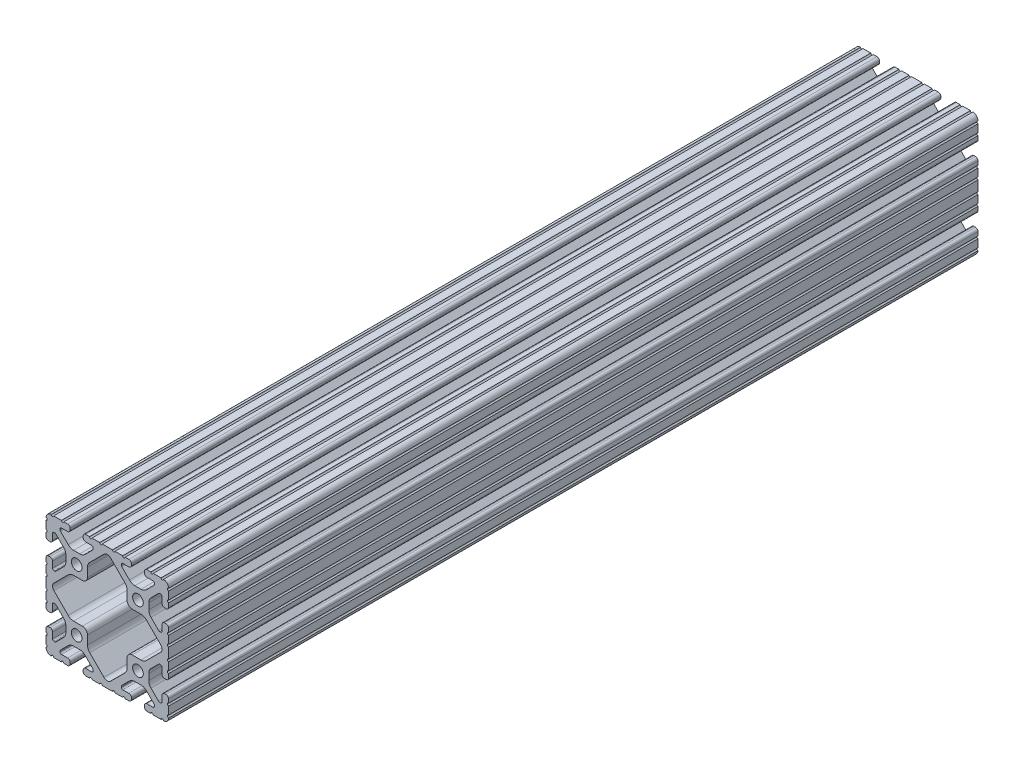
SolidWorks part; units mm, degrees
material "6105-T5 Aluminum"
ref_plane "Front Plane" through (0, 0, 0) normal (0, 0, 1) x (1, 0, 0)
ref_plane "Top Plane" through (0, 0, 0) normal (0, 1, 0) x (1, 0, 0)
ref_plane "Right Plane" through (0, 0, 0) normal (1, 0, 0) x (0, 0, -1)
sketch "Sketch1" plane through (0, 0, 0) normal (0, 0, 1) x (1, 0, 0)
  line L0 (15.487, 12.312) -> (20.9469, 12.312)
  line L1 (24.3055, 10.9208) -> (33.1609, 2.0655)
  line L2 (33.1609, -2.0655) -> (24.3055, -10.9208)
  line L3 (20.9469, -12.312) -> (15.487, -12.312)
  line L4 (12.312, -15.487) -> (12.312, -20.9469)
  line L5 (10.9208, -24.3055) -> (2.0655, -33.1609)
  line L6 (-2.0655, -33.1609) -> (-10.9208, -24.3055)
  line L7 (-12.312, -20.9469) -> (-12.312, -15.487)
  line L8 (-15.487, -12.312) -> (-20.9469, -12.312)
  line L9 (-24.3055, -10.9208) -> (-33.1609, -2.0655)
  line L10 (-33.1609, 2.0655) -> (-24.3055, 10.9208)
  line L11 (-20.9469, 12.312) -> (-15.487, 12.312)
  line L12 (-12.312, 15.487) -> (-12.312, 20.9469)
  line L13 (-10.9208, 24.3055) -> (-2.0655, 33.1609)
  line L14 (2.0655, 33.1609) -> (10.9208, 24.3055)
  line L15 (12.312, 20.9469) -> (12.312, 15.487)
  line L16 (-38.1, 3.2004) -> (-38.1, -3.2004)
  line L17 (-38.1, -4.7244) -> (-38.1, -9.5504)
  line L18 (-38.1, -11.0744) -> (-38.1, -13.4112)
  line L19 (-36.5252, -14.986) -> (-35.6108, -14.986)
  line L20 (-34.036, -13.4112) -> (-34.036, -9.652)
  line L21 (-33.147, -8.763) -> (-32.5789, -8.763)
  line L22 (-31.9503, -9.0234) -> (-27.1792, -13.7945)
  line L23 (-25.788, -17.1531) -> (-25.788, -20.9469)
  line L24 (-27.1792, -24.3055) -> (-31.9503, -29.0766)
  line L25 (-32.5789, -29.337) -> (-33.147, -29.337)
  line L26 (-34.036, -28.448) -> (-34.036, -24.6888)
  line L27 (-35.6108, -23.114) -> (-36.5252, -23.114)
  line L28 (-38.1, -24.6888) -> (-38.1, -27.0256)
  line L29 (-38.1, -28.5496) -> (-38.1, -33.3756)
  line L30 (-38.1, -34.8996) -> (-38.1, -34.925)
  line L31 (-34.925, -38.1) -> (-34.8996, -38.1)
  line L32 (-33.3756, -38.1) -> (-28.5496, -38.1)
  line L33 (-27.0256, -38.1) -> (-24.6888, -38.1)
  line L34 (-23.114, -36.5252) -> (-23.114, -35.6108)
  line L35 (-24.6888, -34.036) -> (-28.448, -34.036)
  line L36 (-29.337, -33.147) -> (-29.337, -32.5789)
  line L37 (-29.0766, -31.9503) -> (-24.3055, -27.1792)
  line L38 (-20.9469, -25.788) -> (-17.1531, -25.788)
  line L39 (-13.7945, -27.1792) -> (-9.0234, -31.9503)
  line L40 (-8.763, -32.5789) -> (-8.763, -33.147)
  line L41 (-9.652, -34.036) -> (-13.4112, -34.036)
  line L42 (-14.986, -35.6108) -> (-14.986, -36.5252)
  line L43 (-13.4112, -38.1) -> (-11.0744, -38.1)
  line L44 (-9.5504, -38.1) -> (-4.7244, -38.1)
  line L45 (-3.2004, -38.1) -> (3.2004, -38.1)
  line L46 (4.7244, -38.1) -> (9.5504, -38.1)
  line L47 (11.0744, -38.1) -> (13.4112, -38.1)
  line L48 (14.986, -36.5252) -> (14.986, -35.6108)
  line L49 (13.4112, -34.036) -> (9.652, -34.036)
  line L50 (8.763, -33.147) -> (8.763, -32.5789)
  line L51 (9.0234, -31.9503) -> (13.7945, -27.1792)
  line L52 (17.1531, -25.788) -> (20.9469, -25.788)
  line L53 (24.3055, -27.1792) -> (29.0766, -31.9503)
  line L54 (29.337, -32.5789) -> (29.337, -33.147)
  line L55 (28.448, -34.036) -> (24.6888, -34.036)
  line L56 (23.114, -35.6108) -> (23.114, -36.5252)
  line L57 (24.6888, -38.1) -> (27.0256, -38.1)
  line L58 (28.5496, -38.1) -> (33.3756, -38.1)
  line L59 (34.8996, -38.1) -> (34.925, -38.1)
  line L60 (38.1, -34.925) -> (38.1, -34.8996)
  line L61 (38.1, -33.3756) -> (38.1, -28.5496)
  line L62 (38.1, -27.0256) -> (38.1, -24.6888)
  line L63 (36.5252, -23.114) -> (35.6108, -23.114)
  line L64 (34.036, -24.6888) -> (34.036, -28.448)
  line L65 (33.147, -29.337) -> (32.5789, -29.337)
  line L66 (31.9503, -29.0766) -> (27.1792, -24.3055)
  line L67 (25.788, -20.9469) -> (25.788, -17.1531)
  line L68 (27.1792, -13.7945) -> (31.9503, -9.0234)
  line L69 (32.5789, -8.763) -> (33.147, -8.763)
  line L70 (34.036, -9.652) -> (34.036, -13.4112)
  line L71 (35.6108, -14.986) -> (36.5252, -14.986)
  line L72 (38.1, -13.4112) -> (38.1, -11.0744)
  line L73 (38.1, -9.5504) -> (38.1, -4.7244)
  line L74 (38.1, -3.2004) -> (38.1, 3.2004)
  line L75 (38.1, 4.7244) -> (38.1, 9.5504)
  line L76 (38.1, 11.0744) -> (38.1, 13.4112)
  line L77 (36.5252, 14.986) -> (35.6108, 14.986)
  line L78 (34.036, 13.4112) -> (34.036, 9.652)
  line L79 (33.147, 8.763) -> (32.5789, 8.763)
  line L80 (31.9503, 9.0234) -> (27.1792, 13.7945)
  line L81 (25.788, 17.1531) -> (25.788, 20.9469)
  line L82 (27.1792, 24.3055) -> (31.9503, 29.0766)
  line L83 (32.5789, 29.337) -> (33.147, 29.337)
  line L84 (34.036, 28.448) -> (34.036, 24.6888)
  line L85 (35.6108, 23.114) -> (36.5252, 23.114)
  line L86 (38.1, 24.6888) -> (38.1, 27.0256)
  line L87 (38.1, 28.5496) -> (38.1, 33.3756)
  line L88 (38.1, 34.8996) -> (38.1, 34.925)
  line L89 (34.925, 38.1) -> (34.8996, 38.1)
  line L90 (33.3756, 38.1) -> (28.5496, 38.1)
  line L91 (27.0256, 38.1) -> (24.6888, 38.1)
  line L92 (23.114, 36.5252) -> (23.114, 35.6108)
  line L93 (24.6888, 34.036) -> (28.448, 34.036)
  line L94 (29.337, 33.147) -> (29.337, 32.5789)
  line L95 (29.0766, 31.9503) -> (24.3055, 27.1792)
  line L96 (20.9469, 25.788) -> (17.1531, 25.788)
  line L97 (13.7945, 27.1792) -> (9.0234, 31.9503)
  line L98 (8.763, 32.5789) -> (8.763, 33.147)
  line L99 (9.652, 34.036) -> (13.4112, 34.036)
  line L100 (14.986, 35.6108) -> (14.986, 36.5252)
  line L101 (13.4112, 38.1) -> (11.0744, 38.1)
  line L102 (9.5504, 38.1) -> (4.7244, 38.1)
  line L103 (3.2004, 38.1) -> (-3.2004, 38.1)
  line L104 (-4.7244, 38.1) -> (-9.5504, 38.1)
  line L105 (-11.0744, 38.1) -> (-13.4112, 38.1)
  line L106 (-14.986, 36.5252) -> (-14.986, 35.6108)
  line L107 (-13.4112, 34.036) -> (-9.652, 34.036)
  line L108 (-8.763, 33.147) -> (-8.763, 32.5789)
  line L109 (-9.0234, 31.9503) -> (-13.7945, 27.1792)
  line L110 (-17.1531, 25.788) -> (-20.9469, 25.788)
  line L111 (-24.3055, 27.1792) -> (-29.0766, 31.9503)
  line L112 (-29.337, 32.5789) -> (-29.337, 33.147)
  line L113 (-28.448, 34.036) -> (-24.6888, 34.036)
  line L114 (-23.114, 35.6108) -> (-23.114, 36.5252)
  line L115 (-24.6888, 38.1) -> (-27.0256, 38.1)
  line L116 (-28.5496, 38.1) -> (-33.3756, 38.1)
  line L117 (-34.8996, 38.1) -> (-34.925, 38.1)
  line L118 (-38.1, 34.925) -> (-38.1, 34.8996)
  line L119 (-38.1, 33.3756) -> (-38.1, 28.5496)
  line L120 (-38.1, 27.0256) -> (-38.1, 24.6888)
  line L121 (-36.5252, 23.114) -> (-35.6108, 23.114)
  line L122 (-34.036, 24.6888) -> (-34.036, 28.448)
  line L123 (-33.147, 29.337) -> (-32.5789, 29.337)
  line L124 (-31.9503, 29.0766) -> (-27.1792, 24.3055)
  line L125 (-25.788, 20.9469) -> (-25.788, 17.1531)
  line L126 (-27.1792, 13.7945) -> (-31.9503, 9.0234)
  line L127 (-32.5789, 8.763) -> (-33.147, 8.763)
  line L128 (-34.036, 9.652) -> (-34.036, 13.4112)
  line L129 (-35.6108, 14.986) -> (-36.5252, 14.986)
  line L130 (-38.1, 13.4112) -> (-38.1, 11.0744)
  line L131 (-38.1, 9.5504) -> (-38.1, 4.7244)
  circle A0 centre (-19.05, 19.05) radius 3.3274
  circle A1 centre (-19.05, -19.05) radius 3.3274
  circle A2 centre (19.05, -19.05) radius 3.3274
  circle A3 centre (19.05, 19.05) radius 3.3274
  arc A4 (12.312, 15.487) -> (15.487, 12.312) centre (15.487, 15.487) ccw
  arc A5 (24.3055, 10.9208) -> (20.9469, 12.312) centre (20.9469, 7.5622) ccw
  arc A6 (33.1609, -2.0655) -> (33.1609, 2.0655) centre (31.0954, 0) ccw
  arc A7 (20.9469, -12.312) -> (24.3055, -10.9208) centre (20.9469, -7.5622) ccw
  arc A8 (15.487, -12.312) -> (12.312, -15.487) centre (15.487, -15.487) ccw
  arc A9 (10.9208, -24.3055) -> (12.312, -20.9469) centre (7.5622, -20.9469) ccw
  arc A10 (-2.0655, -33.1609) -> (2.0655, -33.1609) centre (0, -31.0954) ccw
  arc A11 (-12.312, -20.9469) -> (-10.9208, -24.3055) centre (-7.5622, -20.9469) ccw
  arc A12 (-12.312, -15.487) -> (-15.487, -12.312) centre (-15.487, -15.487) ccw
  arc A13 (-24.3055, -10.9208) -> (-20.9469, -12.312) centre (-20.9469, -7.5622) ccw
  arc A14 (-33.1609, 2.0655) -> (-33.1609, -2.0655) centre (-31.0954, 0) ccw
  arc A15 (-20.9469, 12.312) -> (-24.3055, 10.9208) centre (-20.9469, 7.5622) ccw
  arc A16 (-15.487, 12.312) -> (-12.312, 15.487) centre (-15.487, 15.487) ccw
  arc A17 (-10.9208, 24.3055) -> (-12.312, 20.9469) centre (-7.5622, 20.9469) ccw
  arc A18 (2.0655, 33.1609) -> (-2.0655, 33.1609) centre (0, 31.0954) ccw
  arc A19 (12.312, 20.9469) -> (10.9208, 24.3055) centre (7.5622, 20.9469) ccw
  arc A20 (-38.1, -4.7244) -> (-38.1, -3.2004) centre (-38.1, -3.9624) ccw
  arc A21 (-38.1, -11.0744) -> (-38.1, -9.5504) centre (-38.1, -10.3124) ccw
  arc A22 (-38.1, -13.4112) -> (-36.5252, -14.986) centre (-36.5252, -13.4112) ccw
  arc A23 (-35.6108, -14.986) -> (-34.036, -13.4112) centre (-35.6108, -13.4112) ccw
  arc A24 (-33.147, -8.763) -> (-34.036, -9.652) centre (-33.147, -9.652) ccw
  arc A25 (-31.9503, -9.0234) -> (-32.5789, -8.763) centre (-32.5789, -9.652) ccw
  arc A26 (-25.788, -17.1531) -> (-27.1792, -13.7945) centre (-30.5378, -17.1531) ccw
  arc A27 (-27.1792, -24.3055) -> (-25.788, -20.9469) centre (-30.5378, -20.9469) ccw
  arc A28 (-32.5789, -29.337) -> (-31.9503, -29.0766) centre (-32.5789, -28.448) ccw
  arc A29 (-34.036, -28.448) -> (-33.147, -29.337) centre (-33.147, -28.448) ccw
  arc A30 (-34.036, -24.6888) -> (-35.6108, -23.114) centre (-35.6108, -24.6888) ccw
  arc A31 (-36.5252, -23.114) -> (-38.1, -24.6888) centre (-36.5252, -24.6888) ccw
  arc A32 (-38.1, -28.5496) -> (-38.1, -27.0256) centre (-38.1, -27.7876) ccw
  arc A33 (-38.1, -34.8996) -> (-38.1, -33.3756) centre (-38.1, -34.1376) ccw
  arc A34 (-38.1, -34.925) -> (-34.925, -38.1) centre (-34.925, -34.925) ccw
  arc A35 (-33.3756, -38.1) -> (-34.8996, -38.1) centre (-34.1376, -38.1) ccw
  arc A36 (-27.0256, -38.1) -> (-28.5496, -38.1) centre (-27.7876, -38.1) ccw
  arc A37 (-24.6888, -38.1) -> (-23.114, -36.5252) centre (-24.6888, -36.5252) ccw
  arc A38 (-23.114, -35.6108) -> (-24.6888, -34.036) centre (-24.6888, -35.6108) ccw
  arc A39 (-29.337, -33.147) -> (-28.448, -34.036) centre (-28.448, -33.147) ccw
  arc A40 (-29.0766, -31.9503) -> (-29.337, -32.5789) centre (-28.448, -32.5789) ccw
  arc A41 (-20.9469, -25.788) -> (-24.3055, -27.1792) centre (-20.9469, -30.5378) ccw
  arc A42 (-13.7945, -27.1792) -> (-17.1531, -25.788) centre (-17.1531, -30.5378) ccw
  arc A43 (-8.763, -32.5789) -> (-9.0234, -31.9503) centre (-9.652, -32.5789) ccw
  arc A44 (-9.652, -34.036) -> (-8.763, -33.147) centre (-9.652, -33.147) ccw
  arc A45 (-13.4112, -34.036) -> (-14.986, -35.6108) centre (-13.4112, -35.6108) ccw
  arc A46 (-14.986, -36.5252) -> (-13.4112, -38.1) centre (-13.4112, -36.5252) ccw
  arc A47 (-9.5504, -38.1) -> (-11.0744, -38.1) centre (-10.3124, -38.1) ccw
  arc A48 (-3.2004, -38.1) -> (-4.7244, -38.1) centre (-3.9624, -38.1) ccw
  arc A49 (4.7244, -38.1) -> (3.2004, -38.1) centre (3.9624, -38.1) ccw
  arc A50 (11.0744, -38.1) -> (9.5504, -38.1) centre (10.3124, -38.1) ccw
  arc A51 (13.4112, -38.1) -> (14.986, -36.5252) centre (13.4112, -36.5252) ccw
  arc A52 (14.986, -35.6108) -> (13.4112, -34.036) centre (13.4112, -35.6108) ccw
  arc A53 (8.763, -33.147) -> (9.652, -34.036) centre (9.652, -33.147) ccw
  arc A54 (9.0234, -31.9503) -> (8.763, -32.5789) centre (9.652, -32.5789) ccw
  arc A55 (17.1531, -25.788) -> (13.7945, -27.1792) centre (17.1531, -30.5378) ccw
  arc A56 (24.3055, -27.1792) -> (20.9469, -25.788) centre (20.9469, -30.5378) ccw
  arc A57 (29.337, -32.5789) -> (29.0766, -31.9503) centre (28.448, -32.5789) ccw
  arc A58 (28.448, -34.036) -> (29.337, -33.147) centre (28.448, -33.147) ccw
  arc A59 (24.6888, -34.036) -> (23.114, -35.6108) centre (24.6888, -35.6108) ccw
  arc A60 (23.114, -36.5252) -> (24.6888, -38.1) centre (24.6888, -36.5252) ccw
  arc A61 (28.5496, -38.1) -> (27.0256, -38.1) centre (27.7876, -38.1) ccw
  arc A62 (34.8996, -38.1) -> (33.3756, -38.1) centre (34.1376, -38.1) ccw
  arc A63 (34.925, -38.1) -> (38.1, -34.925) centre (34.925, -34.925) ccw
  arc A64 (38.1, -33.3756) -> (38.1, -34.8996) centre (38.1, -34.1376) ccw
  arc A65 (38.1, -27.0256) -> (38.1, -28.5496) centre (38.1, -27.7876) ccw
  arc A66 (38.1, -24.6888) -> (36.5252, -23.114) centre (36.5252, -24.6888) ccw
  arc A67 (35.6108, -23.114) -> (34.036, -24.6888) centre (35.6108, -24.6888) ccw
  arc A68 (33.147, -29.337) -> (34.036, -28.448) centre (33.147, -28.448) ccw
  arc A69 (31.9503, -29.0766) -> (32.5789, -29.337) centre (32.5789, -28.448) ccw
  arc A70 (25.788, -20.9469) -> (27.1792, -24.3055) centre (30.5378, -20.9469) ccw
  arc A71 (27.1792, -13.7945) -> (25.788, -17.1531) centre (30.5378, -17.1531) ccw
  arc A72 (32.5789, -8.763) -> (31.9503, -9.0234) centre (32.5789, -9.652) ccw
  arc A73 (34.036, -9.652) -> (33.147, -8.763) centre (33.147, -9.652) ccw
  arc A74 (34.036, -13.4112) -> (35.6108, -14.986) centre (35.6108, -13.4112) ccw
  arc A75 (36.5252, -14.986) -> (38.1, -13.4112) centre (36.5252, -13.4112) ccw
  arc A76 (38.1, -9.5504) -> (38.1, -11.0744) centre (38.1, -10.3124) ccw
  arc A77 (38.1, -3.2004) -> (38.1, -4.7244) centre (38.1, -3.9624) ccw
  arc A78 (38.1, 4.7244) -> (38.1, 3.2004) centre (38.1, 3.9624) ccw
  arc A79 (38.1, 11.0744) -> (38.1, 9.5504) centre (38.1, 10.3124) ccw
  arc A80 (38.1, 13.4112) -> (36.5252, 14.986) centre (36.5252, 13.4112) ccw
  arc A81 (35.6108, 14.986) -> (34.036, 13.4112) centre (35.6108, 13.4112) ccw
  arc A82 (33.147, 8.763) -> (34.036, 9.652) centre (33.147, 9.652) ccw
  arc A83 (31.9503, 9.0234) -> (32.5789, 8.763) centre (32.5789, 9.652) ccw
  arc A84 (25.788, 17.1531) -> (27.1792, 13.7945) centre (30.5378, 17.1531) ccw
  arc A85 (27.1792, 24.3055) -> (25.788, 20.9469) centre (30.5378, 20.9469) ccw
  arc A86 (32.5789, 29.337) -> (31.9503, 29.0766) centre (32.5789, 28.448) ccw
  arc A87 (34.036, 28.448) -> (33.147, 29.337) centre (33.147, 28.448) ccw
  arc A88 (34.036, 24.6888) -> (35.6108, 23.114) centre (35.6108, 24.6888) ccw
  arc A89 (36.5252, 23.114) -> (38.1, 24.6888) centre (36.5252, 24.6888) ccw
  arc A90 (38.1, 28.5496) -> (38.1, 27.0256) centre (38.1, 27.7876) ccw
  arc A91 (38.1, 34.8996) -> (38.1, 33.3756) centre (38.1, 34.1376) ccw
  arc A92 (38.1, 34.925) -> (34.925, 38.1) centre (34.925, 34.925) ccw
  arc A93 (33.3756, 38.1) -> (34.8996, 38.1) centre (34.1376, 38.1) ccw
  arc A94 (27.0256, 38.1) -> (28.5496, 38.1) centre (27.7876, 38.1) ccw
  arc A95 (24.6888, 38.1) -> (23.114, 36.5252) centre (24.6888, 36.5252) ccw
  arc A96 (23.114, 35.6108) -> (24.6888, 34.036) centre (24.6888, 35.6108) ccw
  arc A97 (29.337, 33.147) -> (28.448, 34.036) centre (28.448, 33.147) ccw
  arc A98 (29.0766, 31.9503) -> (29.337, 32.5789) centre (28.448, 32.5789) ccw
  arc A99 (20.9469, 25.788) -> (24.3055, 27.1792) centre (20.9469, 30.5378) ccw
  arc A100 (13.7945, 27.1792) -> (17.1531, 25.788) centre (17.1531, 30.5378) ccw
  arc A101 (8.763, 32.5789) -> (9.0234, 31.9503) centre (9.652, 32.5789) ccw
  arc A102 (9.652, 34.036) -> (8.763, 33.147) centre (9.652, 33.147) ccw
  arc A103 (13.4112, 34.036) -> (14.986, 35.6108) centre (13.4112, 35.6108) ccw
  arc A104 (14.986, 36.5252) -> (13.4112, 38.1) centre (13.4112, 36.5252) ccw
  arc A105 (9.5504, 38.1) -> (11.0744, 38.1) centre (10.3124, 38.1) ccw
  arc A106 (3.2004, 38.1) -> (4.7244, 38.1) centre (3.9624, 38.1) ccw
  arc A107 (-4.7244, 38.1) -> (-3.2004, 38.1) centre (-3.9624, 38.1) ccw
  arc A108 (-11.0744, 38.1) -> (-9.5504, 38.1) centre (-10.3124, 38.1) ccw
  arc A109 (-13.4112, 38.1) -> (-14.986, 36.5252) centre (-13.4112, 36.5252) ccw
  arc A110 (-14.986, 35.6108) -> (-13.4112, 34.036) centre (-13.4112, 35.6108) ccw
  arc A111 (-8.763, 33.147) -> (-9.652, 34.036) centre (-9.652, 33.147) ccw
  arc A112 (-9.0234, 31.9503) -> (-8.763, 32.5789) centre (-9.652, 32.5789) ccw
  arc A113 (-17.1531, 25.788) -> (-13.7945, 27.1792) centre (-17.1531, 30.5378) ccw
  arc A114 (-24.3055, 27.1792) -> (-20.9469, 25.788) centre (-20.9469, 30.5378) ccw
  arc A115 (-29.337, 32.5789) -> (-29.0766, 31.9503) centre (-28.448, 32.5789) ccw
  arc A116 (-28.448, 34.036) -> (-29.337, 33.147) centre (-28.448, 33.147) ccw
  arc A117 (-24.6888, 34.036) -> (-23.114, 35.6108) centre (-24.6888, 35.6108) ccw
  arc A118 (-23.114, 36.5252) -> (-24.6888, 38.1) centre (-24.6888, 36.5252) ccw
  arc A119 (-28.5496, 38.1) -> (-27.0256, 38.1) centre (-27.7876, 38.1) ccw
  arc A120 (-34.8996, 38.1) -> (-33.3756, 38.1) centre (-34.1376, 38.1) ccw
  arc A121 (-34.925, 38.1) -> (-38.1, 34.925) centre (-34.925, 34.925) ccw
  arc A122 (-38.1, 33.3756) -> (-38.1, 34.8996) centre (-38.1, 34.1376) ccw
  arc A123 (-38.1, 27.0256) -> (-38.1, 28.5496) centre (-38.1, 27.7876) ccw
  arc A124 (-38.1, 24.6888) -> (-36.5252, 23.114) centre (-36.5252, 24.6888) ccw
  arc A125 (-35.6108, 23.114) -> (-34.036, 24.6888) centre (-35.6108, 24.6888) ccw
  arc A126 (-33.147, 29.337) -> (-34.036, 28.448) centre (-33.147, 28.448) ccw
  arc A127 (-31.9503, 29.0766) -> (-32.5789, 29.337) centre (-32.5789, 28.448) ccw
  arc A128 (-25.788, 20.9469) -> (-27.1792, 24.3055) centre (-30.5378, 20.9469) ccw
  arc A129 (-27.1792, 13.7945) -> (-25.788, 17.1531) centre (-30.5378, 17.1531) ccw
  arc A130 (-32.5789, 8.763) -> (-31.9503, 9.0234) centre (-32.5789, 9.652) ccw
  arc A131 (-34.036, 9.652) -> (-33.147, 8.763) centre (-33.147, 9.652) ccw
  arc A132 (-34.036, 13.4112) -> (-35.6108, 14.986) centre (-35.6108, 13.4112) ccw
  arc A133 (-36.5252, 14.986) -> (-38.1, 13.4112) centre (-36.5252, 13.4112) ccw
  arc A134 (-38.1, 9.5504) -> (-38.1, 11.0744) centre (-38.1, 10.3124) ccw
  arc A135 (-38.1, 3.2004) -> (-38.1, 4.7244) centre (-38.1, 3.9624) ccw
  dimension "D1" = 19.05
  dimension "D2" = 19.05
  dimension "D3" = 19.05
  dimension "D4" = 19.05
extrude "Boss-Extrude1" add sketch "Sketch1" along normal blind 503.174
